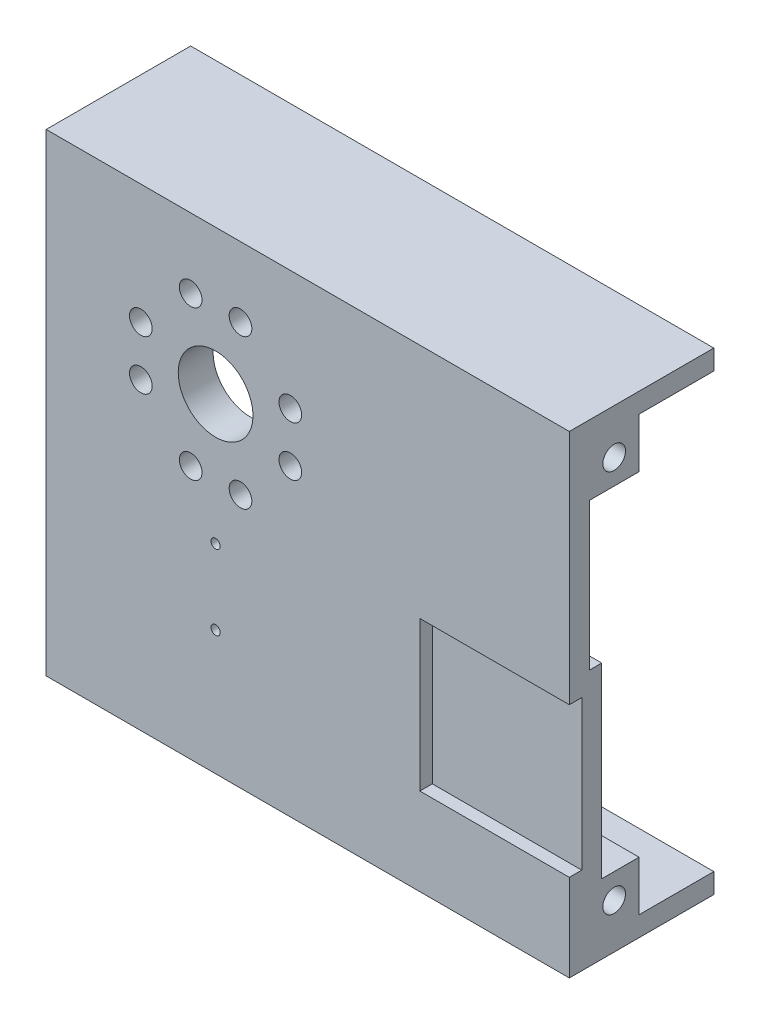
SolidWorks part; units mm, degrees
material "사용자정의 플라스틱"
ref_plane "정면" through (0, 0, 0) normal (0, 0, 1) x (1, 0, 0)
ref_plane "윗면" through (0, 0, 0) normal (0, 1, 0) x (1, 0, 0)
ref_plane "우측면" through (0, 0, 0) normal (1, 0, 0) x (0, 0, -1)
sketch "스케치1" plane through (0, 0, 0) normal (0, 0, 1) x (1, 0, 0)
  line L1 (-105, 95) -> (105, 95)
  line L2 (-105, 95) -> (-105, -95)
  line L3 (-105, -95) -> (105, -95)
  line L4 (105, 95) -> (105, -95)
  line L5 (-105, 95) -> (105, -95) construction
  line L6 (-105, -95) -> (105, 95) construction
  point P0 (0, 0)
  dimension "D1" = 210
  dimension "D2" = 190
extrude "보스-돌출1" add sketch "스케치1" along normal blind 8
sketch "스케치2" plane through (0, 0, 0) normal (0, 0, -1) x (-1, 0, 0)
  line L0 (-105, 95) -> (105, 95)
  line L1 (105, 95) -> (105, -95)
  line L2 (105, -95) -> (-105, -95)
  line L3 (-105, -95) -> (-105, -87)
  line L4 (-105, -95) -> (-105, 95) construction
  line L5 (-105, -87) -> (97, -87)
  line L6 (97, -87) -> (97, 87)
  line L7 (97, 87) -> (-105, 87)
  line L8 (-105, 87) -> (-105, 95)
  dimension "D1" = 8
  dimension "D2" = 8
  dimension "D3" = 8
extrude "보스-돌출2" add sketch "스케치2" along normal blind 50
sketch "스케치3" plane through (105, 0, 0) normal (1, 0, 0) x (0, 0, -1)
  line L1 (0, 87) -> (20, 87)
  line L2 (0, 87) -> (0, 67)
  line L3 (0, 67) -> (20, 67)
  line L4 (20, 87) -> (20, 67)
  dimension "D1" = 20
  dimension "D2" = 20
extrude "보스-돌출3" add sketch "스케치3" against normal blind 15
sketch "스케치8" plane through (105, 0, 0) normal (1, 0, 0) x (0, 0, -1)
  line L0 (0, 67) -> (20, 67) construction
  line L1 (20, 67) -> (20, 87) construction
  circle A0 centre (10, 77) radius 4.55
  dimension "D1" = 9.1
  dimension "D3" = 10
  dimension "D2" = 10
extrude "컷-돌출1" cut sketch "스케치8" against normal blind 25
ref_plane "평면1" through (0, 0, 0) normal (0, -1, 0) x (-1, 0, 0)
mirror "대칭 복사1" about plane through (0, 0, 0) normal (0, -1, 0) of "컷-돌출1", "보스-돌출3"
sketch "스케치9" plane through (0, 0, 0) normal (0, 0, -1) x (-1, 0, 0)
  line L1 (97, -13) -> (-23, -13)
  line L2 (97, -13) -> (97, 87)
  line L3 (97, 87) -> (-23, 87)
  line L4 (-23, -13) -> (-23, 87)
  dimension "D1" = 120
  dimension "D2" = 100
extrude "보스-돌출4" add sketch "스케치9" along normal blind 12
sketch "스케치10" plane through (0, 0, -12) normal (0, 0, -1) x (-1, 0, 0)
  line L0 (97, 87) -> (-23, 87) construction
  line L6 (-23, 87) -> (-23, -13) construction
  circle A0 centre (37, 37) radius 15
  dimension "D3" = 30
  dimension "D2" = 50
  dimension "D1" = 60
extrude "컷-돌출2" cut sketch "스케치10" against normal through all
sketch "스케치13" plane through (0, 0, 8) normal (0, 0, 1) x (1, 0, 0)
  circle A0 centre (-47, 67) radius 4.55
  circle A1 centre (-27, 67) radius 4.55
  circle A2 centre (-37, 37) radius 15 construction
  dimension "D1" = 9.1
  dimension "D2" = 9.1
  dimension "D4" = 30
  dimension "D6" = 10
  dimension "D3" = 10
  dimension "D5" = 30
extrude "컷-돌출3" cut sketch "스케치13" against normal through all
pattern_circular "원형 패턴2" count 4 over 360 about axis through (-37, 37, 0) along (0, 0, 1) of "컷-돌출3"
sketch "스케치14" plane through (0, 0, -12) normal (0, 0, -1) x (-1, 0, 0)
  line L0 (97, 87) -> (-23, 87) construction
  line L1 (-23, 87) -> (97, 87)
  line L2 (-23, 87) -> (-23, -13)
  line L3 (-23, -13) -> (97, -13)
  line L4 (97, 87) -> (97, -13)
  dimension "D1" = 0
extrude "컷-돌출4" cut sketch "스케치14" against normal blind 6
sketch "스케치15" plane through (0, 0, 8) normal (0, 0, 1) x (1, 0, 0)
  line L0 (-105, -95) -> (105, -95) construction
  circle A0 centre (-37, -45) radius 1.85
  circle A1 centre (-37, 37) radius 15 construction
  circle A2 centre (-37, -15) radius 1.85
  dimension "D1" = 0
  dimension "D2" = 3.7
  dimension "D4" = 3.7
  dimension "D3" = 50
  dimension "D5" = 80
extrude "컷-돌출5" cut sketch "스케치15" against normal blind 10
sketch "스케치16" plane through (0, 0, 8) normal (0, 0, 1) x (1, 0, 0)
  line L0 (105, -95) -> (105, 95) construction
  line L1 (37, 8) -> (105, 8)
  line L2 (37, 8) -> (37, -68)
  line L3 (37, -68) -> (105, -68)
  line L4 (105, 8) -> (105, -68)
  line L5 (37, 8) -> (105, -68) construction
  line L6 (37, -68) -> (105, 8) construction
  point P0 (71, -30)
  dimension "D1" = 68
  dimension "D2" = 76
  dimension "D3" = 30
extrude "보스-돌출5" add sketch "스케치16" against normal blind 13
sketch "스케치17" plane through (0, 0, 8) normal (0, 0, 1) x (1, 0, 0)
  line L0 (105, -95) -> (105, 95) construction
  line L1 (45, 0) -> (105, 0)
  line L2 (45, 0) -> (45, -60)
  line L3 (45, -60) -> (105, -60)
  line L4 (105, 0) -> (105, -60)
  line L5 (45, 0) -> (105, -60) construction
  line L6 (45, -60) -> (105, 0) construction
  line L7 (105, 8) -> (37, 8) construction
  line L8 (37, -68) -> (90, -68) construction
  line L9 (37, 8) -> (37, -68) construction
  point P0 (75, -30)
  dimension "D1" = 8
  dimension "D2" = 8
  dimension "D3" = 8
extrude "컷-돌출6" cut sketch "스케치17" against normal blind 5 contours L1 L4 L3 L2
